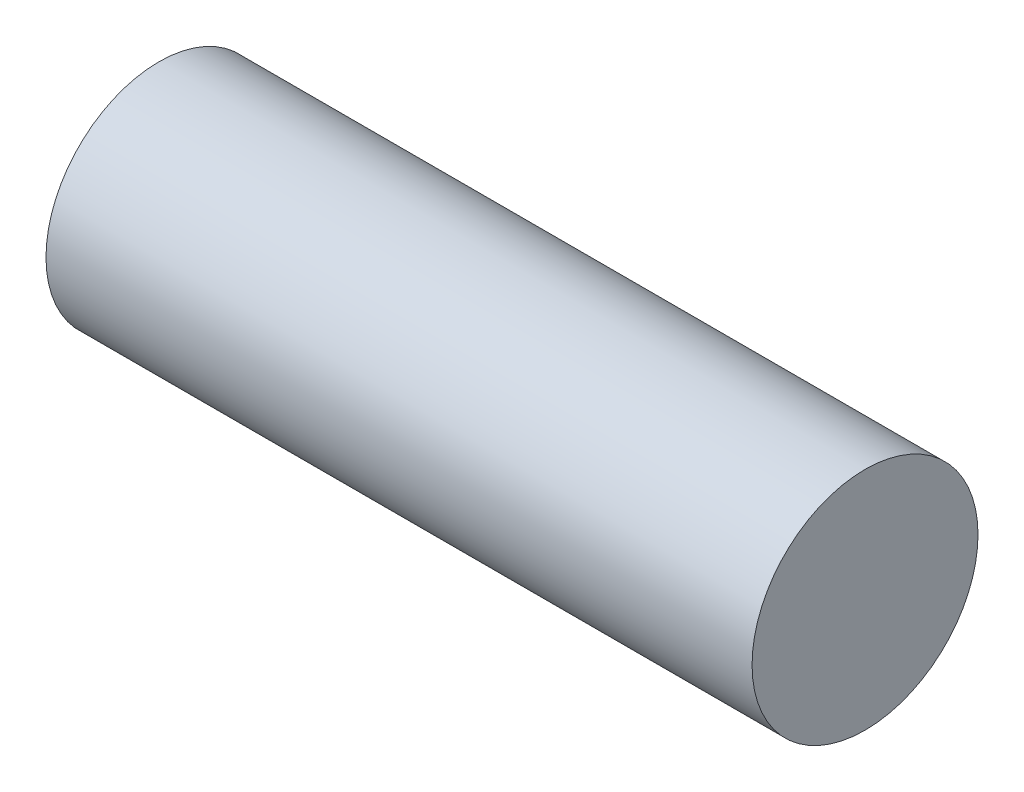
SolidWorks part; units mm, degrees
ref_plane "Front Plane" through (0, 0, 0) normal (0, 0, 1) x (1, 0, 0)
ref_plane "Top Plane" through (0, 0, 0) normal (0, 1, 0) x (1, 0, 0)
ref_plane "Right Plane" through (0, 0, 0) normal (1, 0, 0) x (0, 0, -1)
ref_plane "Plane3" through (30, 0, 0) normal (1, 0, 0) x (0, 0, -1)
ref_plane "Plane4" through (60, 0, 0) normal (1, 0, 0) x (0, 0, -1)
ref_plane "Plane5" through (90, 0, 0) normal (1, 0, 0) x (0, 0, -1)
sketch "Sketch4" plane through (90, 0, 0) normal (1, 0, 0) x (0, 0, -1)
  circle A0 centre (0, 0) radius 30
  dimension "D1" = 60
sketch "Sketch5" plane through (60, 0, 0) normal (1, 0, 0) x (0, 0, -1)
  circle A0 centre (0, 0) radius 20
  dimension "D1" = 40
sketch "Sketch6" plane through (30, 0, 0) normal (1, 0, 0) x (0, 0, -1)
  point P0 (0, 0)
sketch "Sketch8" plane through (0, 0, 0) normal (0, 1, 0) x (1, 0, 0)
  line L0 (60, -20) -> (60, 20) construction
  line L1 (90, -30) -> (90, 30) construction
  spline S0 degree 2 poles (60, 20) (0, 0) (60, -20) knots 0 0 0 1 1 1
  spline S1 degree 1 poles (90, 30) (60, 20) knots 0 0 1 1
  spline S2 degree 1 poles (60, -20) (90, -30) knots 0 0 1 1
ref_plane "Plane6" through (190, 0, 0) normal (1, 0, 0) x (0, 0, -1)
sketch "Sketch9" plane through (190, 0, 0) normal (1, 0, 0) x (0, 0, -1)
  circle A0 centre (0, 0) radius 30
  dimension "D1" = 60
ref_plane "Plane7" through (290, 0, 0) normal (1, 0, 0) x (0, 0, -1)
sketch "Sketch10" plane through (290, 0, 0) normal (1, 0, 0) x (0, 0, -1)
  circle A0 centre (0, 0) radius 30
  dimension "D1" = 60
ref_plane "Plane8" through (340, 0, 0) normal (1, 0, 0) x (0, 0, -1)
ref_plane "Plane9" through (590, 0, 0) normal (1, 0, 0) x (0, 0, -1)
sketch "Sketch18" plane through (590, 0, 0) normal (1, 0, 0) x (0, 0, -1)
  circle A0 centre (-20, 0) radius 11
  dimension "D2" = 22
  dimension "D1" = 20
ref_plane "Plane11" through (610, 0, 0) normal (1, 0, 0) x (0, 0, -1)
sketch "Sketch19" plane through (610, 0, 0) normal (1, 0, 0) x (0, 0, -1)
  circle A0 centre (-20, 0) radius 13.5
  dimension "D1" = 27
sketch "Sketch20" plane through (590, 0, 0) normal (1, 0, 0) x (0, 0, -1)
  circle A0 centre (-20, 0) radius 10
  dimension "D2" = 20
  dimension "D1" = 20
sketch "Sketch21" plane through (610, 0, 0) normal (1, 0, 0) x (0, 0, -1)
  circle A0 centre (-20, 0) radius 12.5
  dimension "D1" = 25
sketch "Sketch23" plane through (0, 0, 0) normal (0, 1, 0) x (1, 0, 0)
  line L0 (594.8009, 0) -> (688.1454, 0) construction
sketch3d "3DSketch1"
  point P0 (995.6384, 14.9968, 78.9709)
  point P1 (995.6384, 14.9968, 78.9709)
  point P2 (995.6384, 14.9968, 78.9709)
  point P3 (995.6384, 14.9968, 78.9709)
  point P4 (995.6384, 14.9968, 78.9709)
  point P5 (995.6384, 14.9968, 78.9709)
  point P6 (995.6384, 14.9968, 78.9709)
sketch "Sketch28" plane through (590, 0, 0) normal (1, 0, 0) x (0, 0, -1)
  circle A0 centre (0, 0) radius 40
sketch "Sketch30" plane through (340, 0, 0) normal (1, 0, 0) x (0, 0, -1)
  circle A0 centre (0, 0) radius 40
loft "Loft2" add profiles "Sketch28", "Sketch30"
